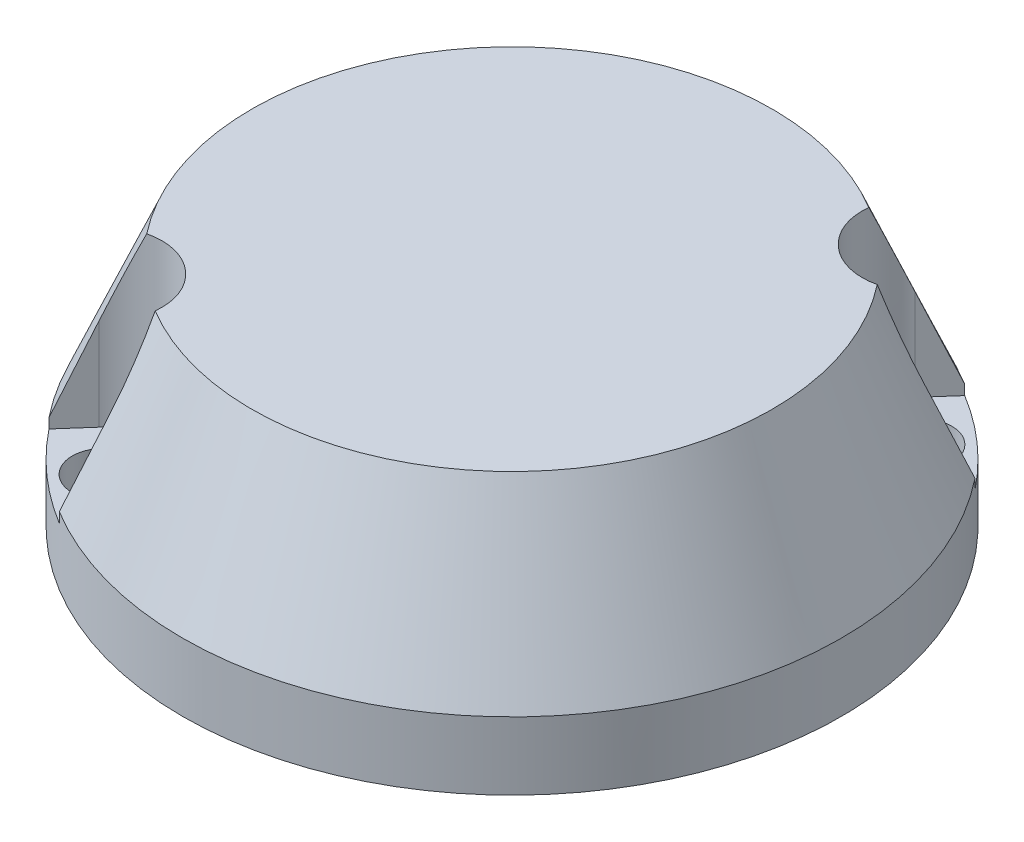
SolidWorks part; units mm, degrees
ref_plane "Front Plane" through (0, 0, 0) normal (0, 0, 1) x (1, 0, 0)
ref_plane "Top Plane" through (0, 0, 0) normal (0, 1, 0) x (1, 0, 0)
ref_plane "Right Plane" through (0, 0, 0) normal (1, 0, 0) x (0, 0, -1)
sketch "Sketch1" plane through (0, 0, 0) normal (0, 1, 0) x (1, 0, 0)
  circle A0 centre (0, 0) radius 11.4
  dimension "D1" = 22.8
extrude "Boss-Extrude1" add sketch "Sketch1" along normal blind 8
sketch "Sketch2" plane through (0, 8, 0) normal (0, 1, 0) x (1, 0, 0)
  circle A0 centre (0, 0) radius 9
  dimension "D1" = 18
extrude "Cut-Extrude1" cut sketch "Sketch2" against normal blind 8 draft 23 flip side to cut
sketch "Sketch3" plane through (0, 0, 0) normal (0, -1, 0) x (1, 0, 0)
  circle A0 centre (0, 0) radius 10 construction
  circle A1 centre (-6.6108, 7.5031) radius 1.1
  dimension "D1" = 20
  dimension "D2" = 2.2
extrude "Cut-Extrude2" cut sketch "Sketch3" against normal blind 8
sketch "Sketch4" plane through (0, 8, 0) normal (0, 1, 0) x (1, 0, 0)
  line L0 (-6.6108, -7.5031) -> (0, 0) construction
  line L2 (-8.1114, -6.181) -> (-10.5324, -8.9287)
  line L3 (-10.5324, -8.9287) -> (-7.5311, -11.5731)
  line L4 (-7.5311, -11.5731) -> (-5.1102, -8.8253)
  arc A0 (-5.1102, -8.8253) -> (-8.1114, -6.181) centre (-6.6108, -7.5031) ccw
  dimension "D1" = 4
extrude "Cut-Extrude3" cut sketch "Sketch4" against normal blind 6
pattern_circular "CirPattern1" count 2 over 360 about axis through (0, 0, 0) along (0, 1, 0) of "Cut-Extrude2", "Cut-Extrude3"
sketch "Sketch5" plane through (0, 0, 0) normal (0, -1, 0) x (1, 0, 0)
  circle A0 centre (0, 0) radius 7.75
  dimension "D1" = 15.5
extrude "Cut-Extrude5" cut sketch "Sketch5" against normal blind 6.5
